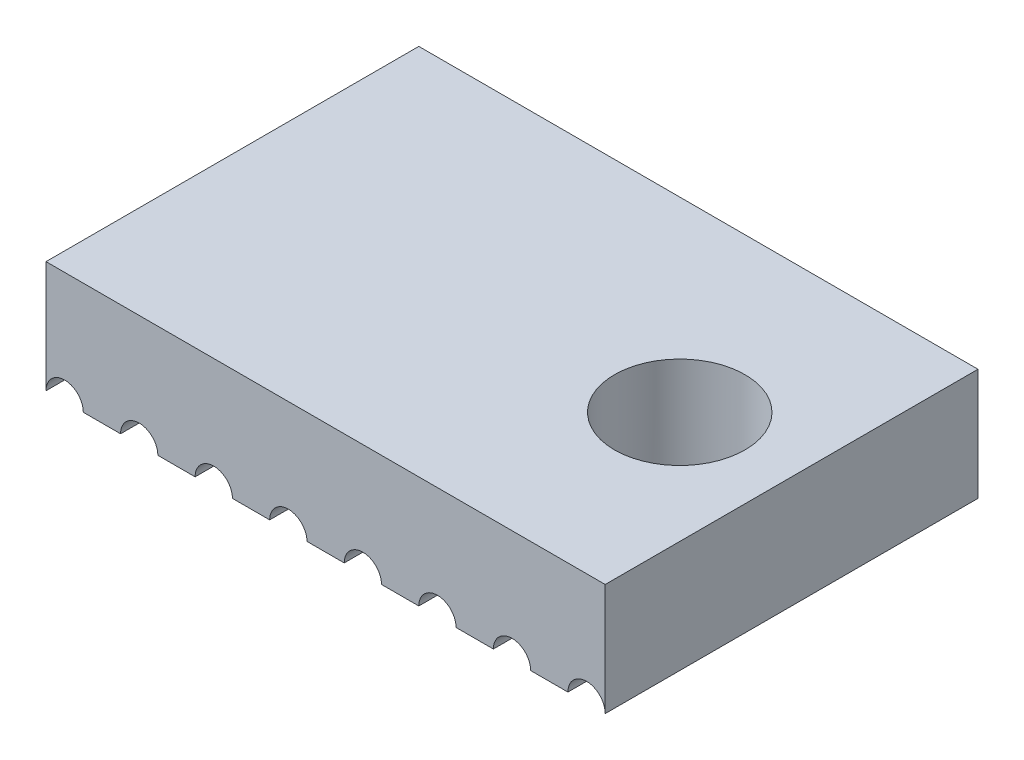
SolidWorks part; units mm, degrees
material "ABS"
ref_plane "Front Plane" through (0, 0, 0) normal (0, 0, 1) x (1, 0, 0)
ref_plane "Top Plane" through (0, 0, 0) normal (0, 1, 0) x (1, 0, 0)
ref_plane "Right Plane" through (0, 0, 0) normal (1, 0, 0) x (0, 0, -1)
sketch "Sketch1" plane through (0, 0, 0) normal (0, 1, 0) x (1, 0, 0)
  line L1 (-7.5, -5) -> (7.5, -5)
  line L2 (-7.5, -5) -> (-7.5, 5)
  line L3 (-7.5, 5) -> (7.5, 5)
  line L4 (7.5, -5) -> (7.5, 5)
  line L5 (-7.5, -5) -> (7.5, 5) construction
  line L6 (-7.5, 5) -> (7.5, -5) construction
  point P0 (0, 0)
  dimension "D1" = 15
  dimension "D2" = 10
extrude "Boss-Extrude1" add sketch "Sketch1" along normal blind 3
sketch "Sketch2" plane through (0, 3, 0) normal (0, 1, 0) x (1, 0, 0)
  line L0 (7.5, -5) -> (7.5, 5) construction
  circle A0 centre (4.5, 0) radius 1.75
  dimension "D1" = 3.5
  dimension "D2" = 3
extrude "Cut-Extrude1" cut sketch "Sketch2" against normal through all
sketch "Sketch3" plane through (0, 0, 5) normal (0, 0, 1) x (1, 0, 0)
  line L1 (-7.5, 0) -> (7.5, 0) construction
  line L2 (-7.5, 0) -> (-6.5, 0)
  line L3 (-5.5, 0) -> (-4.5, 0)
  arc A0 (-7.5, 0) -> (-6.5, 0) centre (-7, 0) cw
  arc A1 (-5.5, 0) -> (-4.5, 0) centre (-5, 0) cw
  dimension "D1" = 0.5
  dimension "D3" = 1
  dimension "D2" = 0.5
extrude "Cut-Extrude2" cut sketch "Sketch3" against normal through all
pattern_linear "LPattern1" count 7 spacing 2 along (1, 0, 0) of "Cut-Extrude2"
equation "\"`\"=0.655244"
